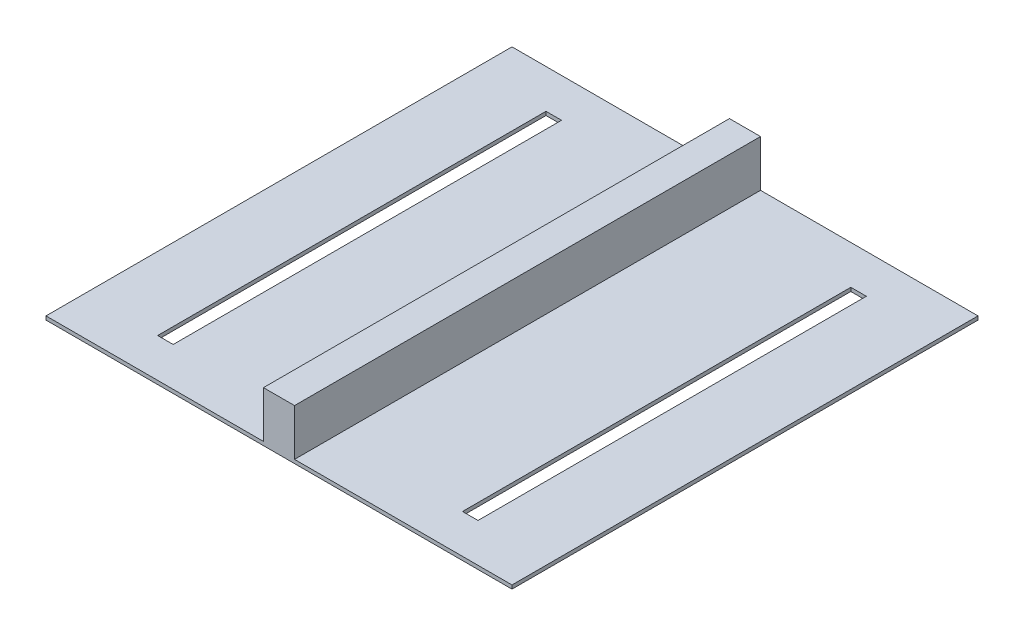
SolidWorks part; units mm, degrees
material "Cedar"
ref_plane "Front Plane" through (0, 0, 0) normal (0, 0, 1) x (1, 0, 0)
ref_plane "Top Plane" through (0, 0, 0) normal (0, 1, 0) x (1, 0, 0)
ref_plane "Right Plane" through (0, 0, 0) normal (1, 0, 0) x (0, 0, -1)
sketch "Sketch1" plane through (0, 0, 0) normal (0, 1, 0) x (1, 0, 0)
  line L5 (-381, 381) -> (381, 381)
  line L6 (-381, 381) -> (-381, -381)
  line L7 (-381, -381) -> (381, -381)
  line L8 (381, 381) -> (381, -381)
  line L9 (-261.9248, 317.5) -> (-236.5248, 317.5)
  line L10 (-261.9248, 317.5) -> (-261.9248, -317.5)
  line L11 (-261.9248, -317.5) -> (-236.5248, -317.5)
  line L12 (-236.5248, 317.5) -> (-236.5248, -317.5)
  line L13 (236.5248, 317.5) -> (261.9248, 317.5)
  line L14 (236.5248, 317.5) -> (236.5248, -317.5)
  line L15 (236.5248, -317.5) -> (261.9248, -317.5)
  line L16 (261.9248, 317.5) -> (261.9248, -317.5)
  dimension "D1" = 762
  dimension "D2" = 762
  dimension "D3" = 381
  dimension "D4" = 381
  dimension "D5" = 119.0752
  dimension "D6" = 63.5
  dimension "D7" = 25.4
  dimension "D8" = 63.5
  dimension "D9" = 63.5
  dimension "D10" = 63.5
  dimension "D11" = 119.0752
  dimension "D12" = 25.4
extrude "Boss-Extrude1" add sketch "Sketch1" along normal mid plane 6
sketch "Sketch2" plane through (0, 3, 0) normal (0, 1, 0) x (1, 0, 0)
  line L0 (381, 381) -> (-381, 381) construction
  line L1 (-25.4, 381) -> (25.4, 381)
  line L2 (-25.4, 381) -> (-25.4, -381)
  line L3 (-25.4, -381) -> (25.4, -381)
  line L4 (25.4, 381) -> (25.4, -381)
  line L5 (-381, -381) -> (381, -381) construction
  dimension "D1" = 50.8
  dimension "D2" = 25.4
extrude "Boss-Extrude2" add sketch "Sketch2" along normal blind 76.2
